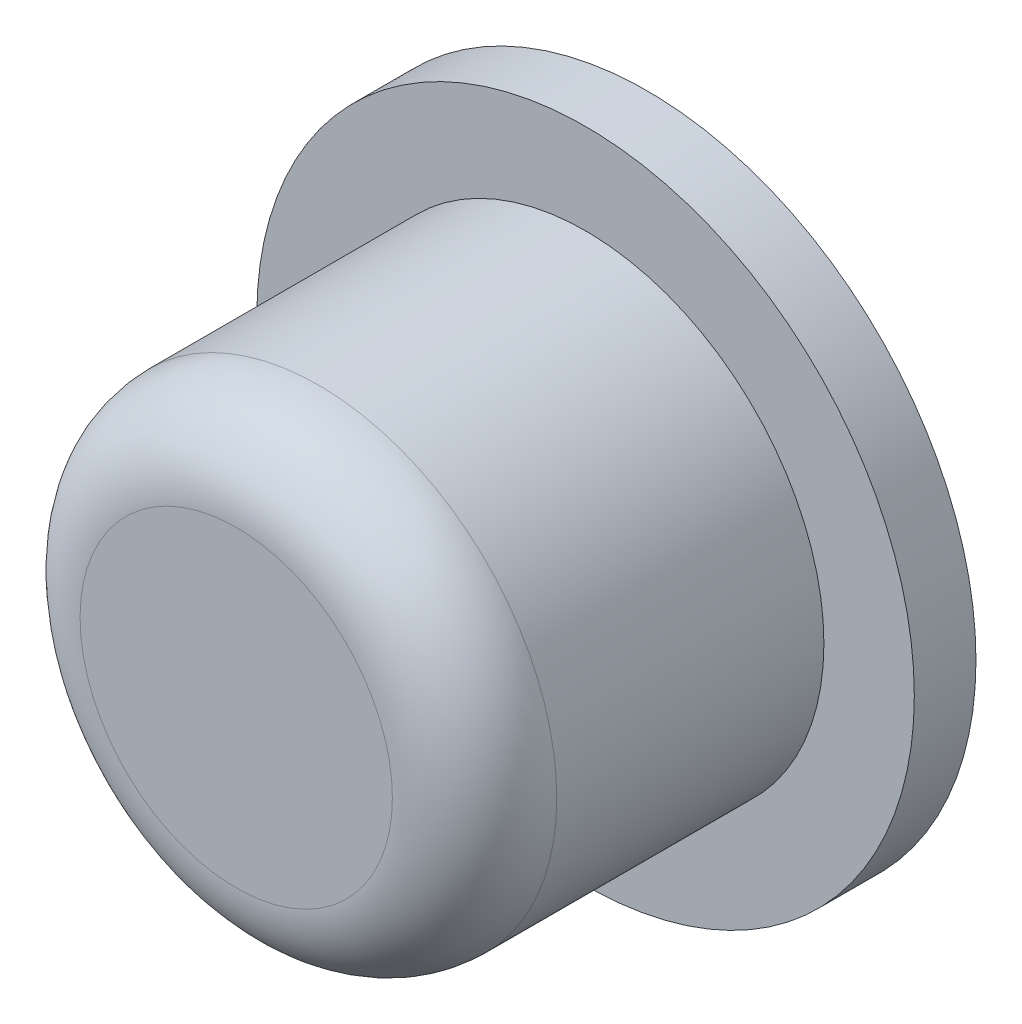
SolidWorks part; units mm, degrees
material "ABS"
ref_plane "Płaszczyzna przednia" through (0, 0, 0) normal (0, 0, 1) x (1, 0, 0)
ref_plane "Płaszczyzna górna" through (0, 0, 0) normal (0, 1, 0) x (1, 0, 0)
ref_plane "Płaszczyzna prawa" through (0, 0, 0) normal (1, 0, 0) x (0, 0, -1)
sketch "Szkic1" plane through (0, 0, 0) normal (0, 0, 1) x (1, 0, 0)
  circle A0 centre (0, 0) radius 4
  dimension "D1" = 8
extrude "Dodanie-wyciągnięcie1" add sketch "Szkic1" along normal blind 0.75
sketch "Szkic2" plane through (0, 0, 0.75) normal (0, 0, 1) x (1, 0, 0)
  circle A0 centre (0, 0) radius 2.9
  dimension "D1" = 5.8
extrude "Dodanie-wyciągnięcie2" add sketch "Szkic2" along normal blind 4.25
sketch "Szkic3" plane through (0, 0, 0) normal (0, 0, -1) x (-1, 0, 0)
  line L1 (-1.25, 1.25) -> (1.25, 1.25)
  line L2 (-1.25, 1.25) -> (-1.25, -1.25)
  line L3 (-1.25, -1.25) -> (1.25, -1.25)
  line L4 (1.25, 1.25) -> (1.25, -1.25)
  line L5 (-1.25, 1.25) -> (1.25, -1.25) construction
  line L6 (-1.25, -1.25) -> (1.25, 1.25) construction
  point P0 (0, 0)
  dimension "D1" = 2.5
extrude "Wytnij-wyciągnięcie1" cut sketch "Szkic3" against normal blind 1
fillet "Zaokrąglenie1" [suppressed] radius 1
fillet "Zaokrąglenie2" radius 1 1 edges at (2.9, 0, 5)
sketch "Szkic4" plane through (0, 0, 0) normal (0, 0, -1) x (-1, 0, 0)
  line L8 (1.45, 1.45) -> (-1.45, 1.45)
  line L9 (-1.45, 1.45) -> (-1.45, -1.45)
  line L10 (-1.45, -1.45) -> (1.45, -1.45)
  line L11 (1.45, -1.45) -> (1.45, 1.45)
  line L12 (1.45, 1.45) -> (-1.45, 1.45)
  line L13 (-1.45, 1.45) -> (-1.45, -1.45)
  line L14 (-1.45, -1.45) -> (1.45, -1.45)
  line L15 (1.45, -1.45) -> (1.45, 1.45)
  dimension "D1" = 0.2
extrude "Wytnij-wyciągnięcie2" cut sketch "Szkic4" against normal up to surface (1 mm away) up to face at (0, 0, 1)
